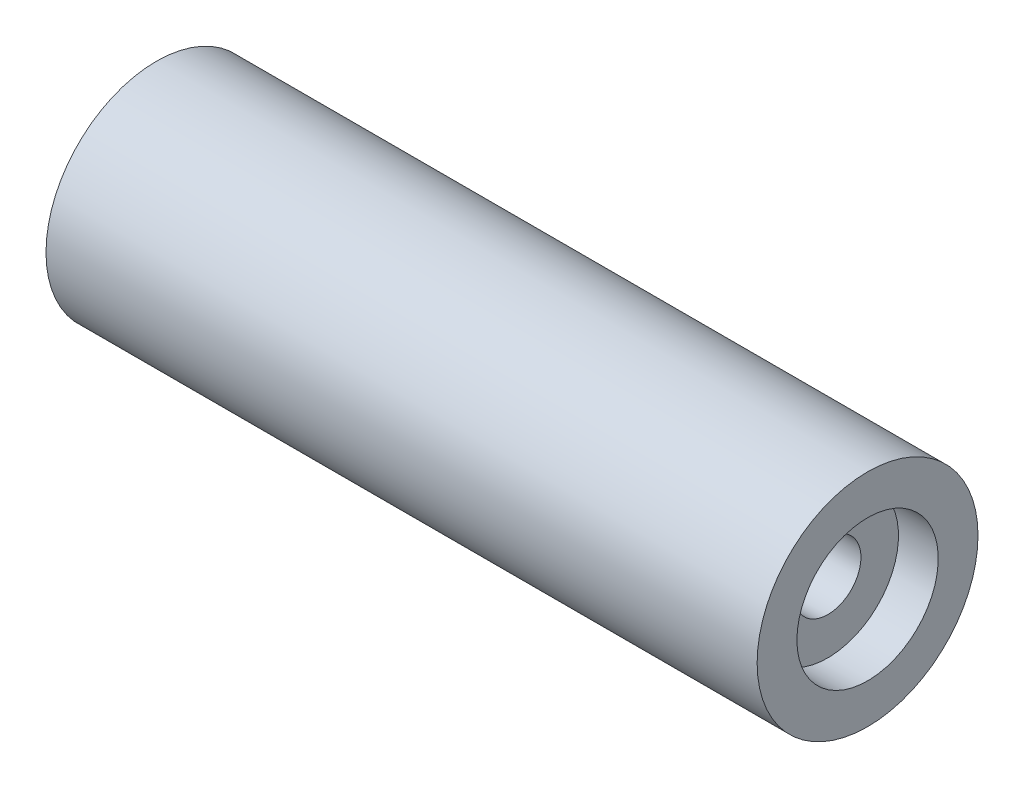
SolidWorks part; units mm, degrees
material "AISI 304"
ref_plane "Ön Düzlem" through (0, 0, 0) normal (0, 0, 1) x (1, 0, 0)
ref_plane "Üst Düzlem" through (0, 0, 0) normal (0, 1, 0) x (1, 0, 0)
ref_plane "Sağ Düzlem" through (0, 0, 0) normal (1, 0, 0) x (0, 0, -1)
sketch "Sketch1" plane through (0, 0, 0) normal (1, 0, 0) x (0, 0, -1)
  circle A0 centre (0, 0) radius 7.5
  circle A1 centre (0, 0) radius 25
  dimension "D1" = 50
  dimension "D2" = 15
extrude "Boss-Extrude1" add sketch "Sketch1" along normal mid plane 161
sketch "Sketch2" plane through (-80.5, 0, 0) normal (-1, 0, 0) x (0, 0, 1)
  circle A0 centre (0, 0) radius 16
  dimension "D1" = 32
extrude "Cut-Extrude1" cut sketch "Sketch2" against normal blind 9
mirror "Mirror1" about plane through (0, 0, 0) normal (1, 0, 0) of "Cut-Extrude1"
